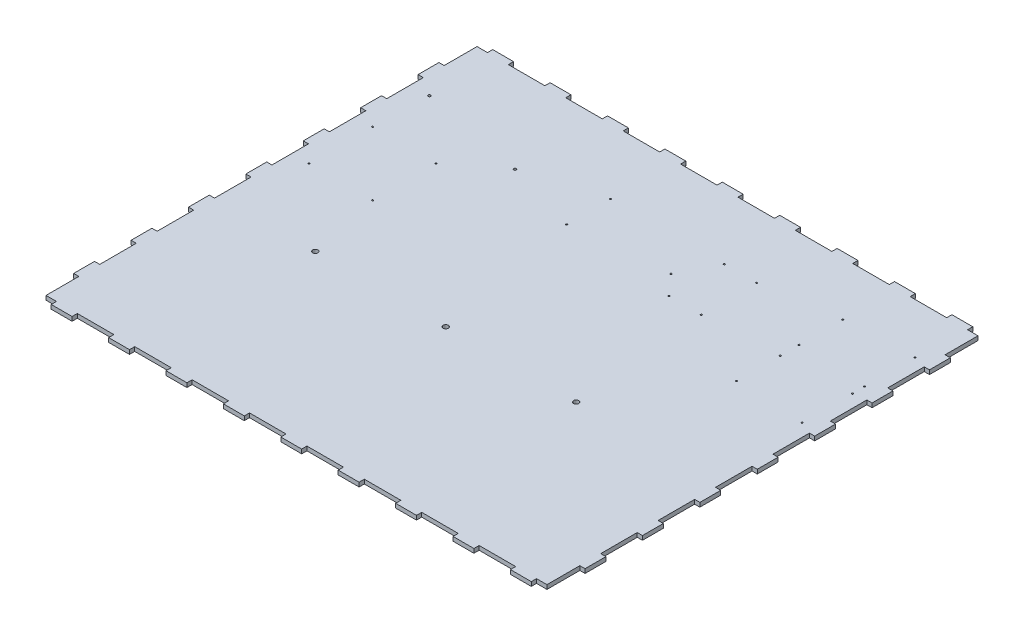
SolidWorks part; units mm, degrees
material "Acrylic (Medium-high impact)"
ref_plane "Front Plane" through (0, 0, 0) normal (0, 0, 1) x (1, 0, 0)
ref_plane "Top Plane" through (0, 0, 0) normal (0, 1, 0) x (1, 0, 0)
ref_plane "Right Plane" through (0, 0, 0) normal (1, 0, 0) x (0, 0, -1)
sketch "Sketch1" plane through (0, 0, 0) normal (0, 1, 0) x (1, 0, 0)
  line L1 (240, -206.5) -> (-240, -206.5)
  line L2 (240, -206.5) -> (240, 206.5)
  line L3 (240, 206.5) -> (-240, 206.5)
  line L4 (-240, -206.5) -> (-240, 206.5)
  line L5 (240, -206.5) -> (-240, 206.5) construction
  line L6 (240, 206.5) -> (-240, -206.5) construction
  point P0 (0, 0)
  dimension "D1" = 480
  dimension "D2" = 413
extrude "Base" add sketch "Sketch1" along normal blind 4
sketch "Sketch2" plane through (0, 4, 0) normal (0, 1, 0) x (1, 0, 0)
  line L0 (240, 206.5) -> (-240, 206.5) construction
  line L1 (-10, 206.5) -> (10, 206.5)
  line L2 (-10, 206.5) -> (-10, 211.5)
  line L3 (-10, 211.5) -> (10, 211.5)
  line L4 (10, 206.5) -> (10, 211.5)
  point P6 (0, 206.5)
  dimension "D1" = 20
  dimension "D2" = 5
extrude "Top Tabs Definition" add sketch "Sketch2" along direction (0, -1, 0) on the side against the normal up to surface (4 mm away)
pattern_linear "Top Tabs Pattern" count 5 spacing 55 along (-1, 0, 0) count 5 spacing 55 along (1, 0, 0) of "Top Tabs Definition"
mirror "Bottom Tabs" about plane through (0, 0, 0) normal (0, 0, 1) of "Top Tabs Definition", "Top Tabs Pattern"
sketch "Sketch3" plane through (0, 4, 0) normal (0, 1, 0) x (1, 0, 0)
  point P0 (59.05, 144.3542)
  point P1 (90.05, 91.3542)
  point P3 (59.05, 91.3542)
  point P4 (41.55, 110.8542)
  point P5 (90.05, 144.3542)
  point P6 (-49.45, 143.8542)
  point P7 (-49.45, 101.8542)
  point P8 (161.815, 95.1308)
  point P9 (227.855, 98.3058)
  point P11 (161.815, 53.2208)
  point P13 (227.855, 50.0458)
  point P15 (227.855, 158.3058)
  point P17 (161.815, 155.1308)
  point P19 (161.815, 113.2208)
  point P21 (227.855, 110.0458)
hole_wizard "Electronics Mounting Holes (1.5)" positions "Sketch4" profile "Sketch5" hole size "Ø1.5" standard "ANSI Metric" end condition up to next
sketch "Sketch4" plane through (0, 4, 0) normal (0, 1, 0) x (1, 0, 0)
  point P0 (-49.45, 143.8542)
  point P2 (-49.45, 101.8542)
  point P4 (41.55, 110.8542)
  point P6 (59.05, 144.3542)
  point P8 (90.05, 144.3542)
  point P10 (90.05, 91.3542)
  point P12 (59.05, 91.3542)
  point P14 (161.815, 95.1308)
  point P16 (161.815, 53.2208)
  point P18 (161.815, 155.1308)
  point P20 (161.815, 113.2208)
  point P22 (227.855, 110.0458)
  point P24 (227.855, 158.3058)
  point P26 (227.855, 50.0458)
  point P28 (227.855, 98.3058)
  point P62 (-162.5, 28.8542)
  point P64 (-162.5, 89.8542)
  point P66 (-223.5, 89.8542)
  point P68 (-223.5, 28.8542)
sketch "Sketch5" plane through (-49.45, 4, -143.8542) normal (1, 0, 0) x (0, 0, 1)
  line L0 (0, 0) -> (0, 4)
  line L1 (0, 4) -> (0.75, 4)
  line L2 (0.75, 4) -> (0.75, 0)
  line L5 (0.75, 0) -> (0, 0)
  line L11 (0, -6.35) -> (0, 107.95) construction
  dimension "Thru Hole Dia." = 1.5
  dimension "Thru Hole Depth" = 4
sketch "Sketch7" plane through (0, 4, 0) normal (0, 1, 0) x (1, 0, 0)
  line L0 (-240, 206.5) -> (-240, -206.5) construction
  line L1 (-240, -10) -> (-245, -10)
  line L2 (-240, -10) -> (-240, 10)
  line L3 (-240, 10) -> (-245, 10)
  line L4 (-245, -10) -> (-245, 10)
  point P6 (-240, 0)
  dimension "D1" = 20
  dimension "D2" = 5
extrude "Left Tabs Definition" add sketch "Sketch7" against normal up to surface (4 mm away) up to face at (-49.45, 0, -143.1042)
pattern_linear "Left Tabs Pattern" count 4 spacing 55 along (0, 0, -1) count 4 spacing 55 along (0, 0, 1) of "Left Tabs Definition"
mirror "Right Tabs" about plane through (0, 0, 0) normal (1, 0, 0) of "Left Tabs Pattern", "Left Tabs Definition"
hole_wizard "M6 Clearance Hole1" positions "Sketch8" profile "Sketch9" hole size "M6x1.0" standard "ANSI Metric" end condition up to next
sketch "Sketch8" plane through (0, 4, 0) normal (0, 1, 0) x (1, 0, 0)
  circle A0 centre (-147.5, -40.9693) radius 5.5 construction
  circle A1 centre (-22.5, -40.9693) radius 5.5 construction
  circle A2 centre (102.5, -40.9693) radius 5.5 construction
  point P0 (-147.5, -40.9693)
  point P10 (-22.5, -40.9693)
  point P12 (102.5, -40.9693)
sketch "Sketch9" plane through (-147.5, 4, 40.9693) normal (1, 0, 0) x (0, 0, 1)
  line L0 (0, 0) -> (0, 4)
  line L1 (0, 4) -> (2.5, 4)
  line L2 (2.5, 4) -> (2.5, 0)
  line L5 (2.5, 0) -> (0, 0)
  line L11 (0, -6.35) -> (0, 107.95) construction
  dimension "Thru Hole Dia." = 5
  dimension "Thru Hole Depth" = 4
hole_wizard "Tap Drill for M3x0.5 Tap1" positions "Sketch10" profile "Sketch11" hole size "M3x0.5" standard "ANSI Metric" end condition up to next
sketch "Sketch10" plane through (0, 0, 0) normal (0, -1, 0) x (-1, 0, 0)
  circle A0 centre (222, 142.8542) radius 1.6 construction
  circle A1 centre (120, 122.8542) radius 1.6 construction
  point P0 (120, 122.8542)
  point P2 (222, 142.8542)
sketch "Sketch11" plane through (-120, 0, -122.8542) normal (1, 0, 0) x (0, 0, -1)
  line L0 (0, 0) -> (0, 4)
  line L1 (0, 4) -> (1.25, 4)
  line L2 (1.25, 4) -> (1.25, 0)
  line L5 (1.25, 0) -> (0, 0)
  line L11 (0, -6.35) -> (0, 107.95) construction
  dimension "Thru Hole Dia." = 2.5
  dimension "Thru Hole Depth" = 4
